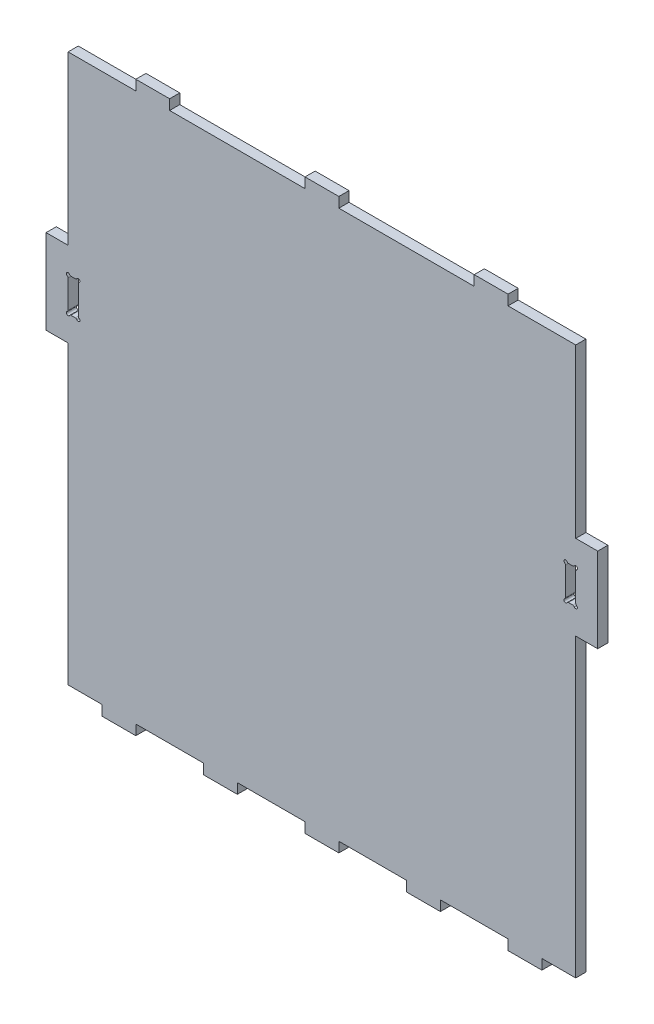
SolidWorks part; units mm, degrees
ref_plane "Front Plane" through (0, 0, 0) normal (0, 0, 1) x (1, 0, 0)
ref_plane "Top Plane" through (0, 0, 0) normal (0, 1, 0) x (1, 0, 0)
ref_plane "Right Plane" through (0, 0, 0) normal (1, 0, 0) x (0, 0, -1)
sketch "Sketch1" plane through (0, 0, 0) normal (0, 0, 1) x (1, 0, 0)
  line L0 (0, 0) -> (0, 65) construction
  line L1 (0, 0) -> (0, -103) construction
  line L2 (-75, 65) -> (0, 65) construction
  line L3 (-75, -103) -> (75, -103) construction
  line L4 (-5, 65) -> (5, 65)
  line L5 (-5, 65) -> (-5, 62)
  line L6 (-5, 62) -> (-45, 62)
  line L7 (-45, 62) -> (-45, 65)
  line L8 (-45, 65) -> (-55, 65)
  line L9 (-55, 65) -> (-55, 62)
  line L10 (-55, 62) -> (-75, 62)
  line L11 (5, 65) -> (5, 62)
  line L12 (5, 65) -> (75, 65) construction
  line L13 (5, 62) -> (45, 62)
  line L14 (45, 62) -> (45, 65)
  line L15 (55, 65) -> (55, 62)
  line L16 (45, 65) -> (55, 65)
  line L17 (55, 62) -> (75, 62)
  line L18 (5, -103) -> (-5, -103)
  line L19 (-5, -103) -> (-5, -100)
  line L20 (-5, -100) -> (-25, -100)
  line L21 (-25, -100) -> (-25, -103)
  line L22 (-25, -103) -> (-35, -103)
  line L23 (-35, -103) -> (-35, -100)
  line L24 (-35, -100) -> (-55, -100)
  line L25 (-55, -100) -> (-55, -103)
  line L26 (-55, -103) -> (-65, -103)
  line L27 (-65, -103) -> (-65, -100)
  line L28 (-65, -100) -> (-75, -100)
  line L29 (5, -103) -> (5, -100)
  line L30 (5, -100) -> (25, -100)
  line L31 (25, -100) -> (25, -103)
  line L32 (25, -103) -> (35, -103)
  line L33 (35, -103) -> (35, -100)
  line L34 (35, -100) -> (55, -100)
  line L35 (55, -100) -> (55, -103)
  line L36 (55, -103) -> (65, -103)
  line L37 (65, -103) -> (65, -100)
  line L38 (65, -100) -> (75, -100)
  line L39 (-75, 62) -> (-75, -100) construction
  line L40 (0, 0) -> (-75, 0) construction
  line L42 (-75, 12.5) -> (-81.5, 12.5)
  line L43 (-81.5, 12.5) -> (-81.5, -12.5)
  line L44 (-81.5, -12.5) -> (-75, -12.5)
  line L45 (-75, 62) -> (-75, 12.5)
  line L50 (-75, -5) -> (-75, 5)
  line L51 (-75, 5) -> (-72, 5)
  line L52 (-75, -12.5) -> (-75, -100)
  line L57 (75, -12.5) -> (75, -100)
  line L58 (81.5, -12.5) -> (75, -12.5)
  line L59 (81.5, 12.5) -> (81.5, -12.5)
  line L60 (75, 12.5) -> (81.5, 12.5)
  line L61 (75, 62) -> (75, 12.5)
  line L62 (-72, 5) -> (-72, -5)
  line L63 (-72, -5) -> (-75, -5)
  line L64 (72, 5) -> (72, -5)
  line L65 (75, 5) -> (72, 5)
  line L66 (75, -5) -> (75, 5)
  line L67 (72, -5) -> (75, -5)
  point P4 (0, 0)
  point P9 (0, 65)
  point P12 (0, -103)
  point P15 (0, 65)
  point P52 (-75, 0)
  point P57 (-75, 0)
  dimension "D1" = 65
  dimension "D2" = 103
  dimension "D3" = 150
  dimension "D4" = 150
  dimension "D5" = 5
  dimension "D6" = 3
  dimension "D7" = 40
  dimension "D8" = 10
  dimension "D9" = 5
  dimension "D10" = 3
  dimension "D11" = 20
  dimension "D12" = 10
  dimension "D13" = 20
  dimension "D14" = 10
  dimension "D15" = 75
  dimension "D16" = 6.5
  dimension "D17" = 25
  dimension "D18" = 10
  dimension "D19" = 3
  dimension "D20" = 49.5
extrude "Boss-Extrude2" add sketch "Sketch1" along normal blind 3
sketch "Sketch2" plane through (0, 0, 3) normal (0, 0, 1) x (1, 0, 0)
  circle A4 centre (-72, 5) radius 0.5
  circle A5 centre (-72, -5) radius 0.5
  circle A6 centre (-75, 5) radius 0.5
  circle A7 centre (-75, -5) radius 0.5
  circle A8 centre (75, -5) radius 0.5
  circle A9 centre (72, -5) radius 0.5
  circle A10 centre (72, 5) radius 0.5
  circle A11 centre (75, 5) radius 0.5
  dimension "D1" = 1
extrude "Cut-Extrude1" cut sketch "Sketch2" against normal through all
fillet "Fillet1" radius 0.5 16 edges at (75, 4.5, 1.5) (74.5, 5, 1.5) (72, 4.5, 1.5) (72.5, 5, 1.5) (72, -4.5, 1.5) (75, -4.5, 1.5) (72.5, -5, 1.5) (74.5, -5, 1.5) (-72, -4.5, 1.5) (-72.5, -5, 1.5) (-74.5, -5, 1.5) (-75, -4.5, 1.5) (-74.5, 5, 1.5) (-75, 4.5, 1.5) (-72.5, 5, 1.5) (-72, 4.5, 1.5)
